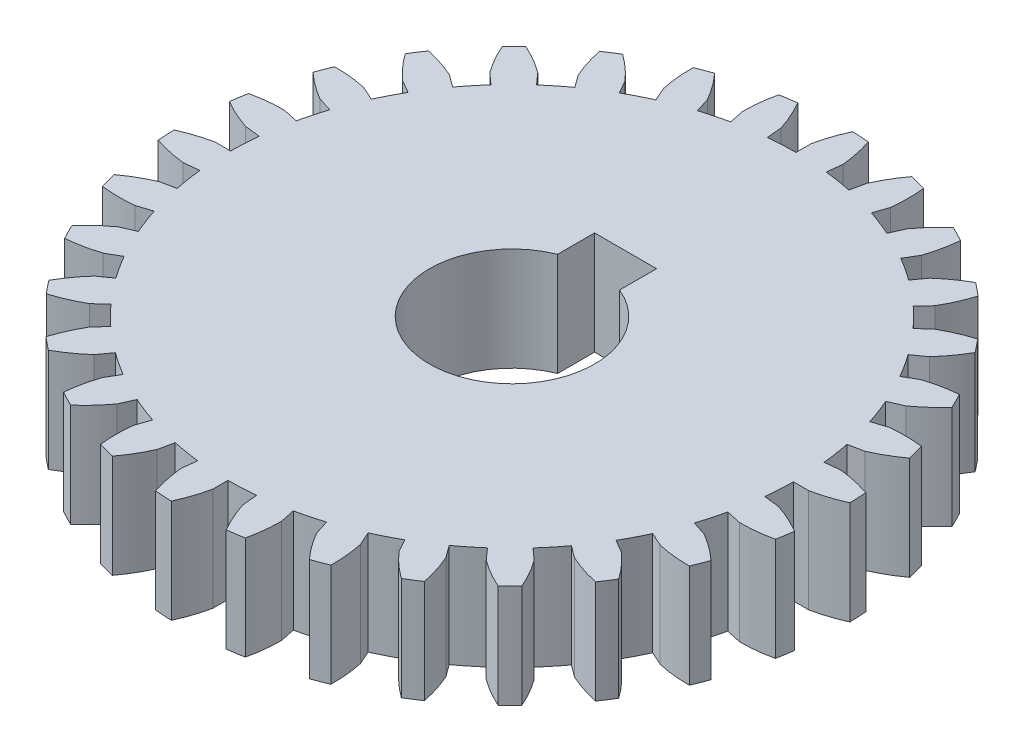
SolidWorks part; units mm, degrees
ref_plane "Front Plane" through (0, 0, 0) normal (0, 0, 1) x (1, 0, 0)
ref_plane "Top Plane" through (0, 0, 0) normal (0, 1, 0) x (1, 0, 0)
ref_plane "Right Plane" through (0, 0, 0) normal (1, 0, 0) x (0, 0, -1)
sketch "Sketch1" plane through (0, 0, 0) normal (0, 1, 0) x (1, 0, 0)
  circle A3 centre (0, 0) radius 13.75
  circle A4 centre (0, 0) radius 16
  circle A5 centre (0, 0) radius 15
  circle A6 centre (0, 0) radius 14
  circle A7 centre (0, 0) radius 14.4889
  dimension "pitch circle" = 30
  dimension "addendum circle" = 32
  dimension "root circle" = 27.5
  dimension "clearance circle" = 28
  dimension "base circle" = 28.9778
sketch "Sketch2" plane through (0, 0, 0) normal (0, 1, 0) x (1, 0, 0)
  line L0 (0, 0) -> (0, 14.4889)
  line L1 (0, 0) -> (7.2444, 12.5477) construction
  line L2 (0, 0) -> (12.5477, 7.2444) construction
  line L3 (0, 0) -> (14.4889, 0) construction
  line L4 (14.4889, 0) -> (14.4889, 22.7591) construction
  line L5 (12.5477, 7.2444) -> (4.9614, 20.3844) construction
  line L6 (7.2444, 12.5477) -> (0.6745, 16.3409) construction
  line L7 (0, 0) -> (3.1187, 14.6722)
  line L8 (0, 0) -> (1.5679, 14.9178) construction
  line L9 (0.8496, 14.9759) -> (0, 0) construction
  circle A0 centre (0, 0) radius 14.4889 construction
  circle A1 centre (0, 0) radius 15 construction
  arc A2 (1.5679, 14.9178) -> (0.1294, 14.9994) centre (0, 0) ccw
  spline S0 degree 3 poles (0, 14.4889) (1.2745, 20.4223) (9.5995, 22.7668) (14.4889, 22.7591) knots 0 0 0 0 1 1 1 1
  spline S1 degree 3 poles (1.6388, 14.3959) (1.0435, 20.4354) (-6.9629, 23.7065) (-11.8218, 24.2518) knots 0 0 0 0 1 1 1 1
  point P11 (0, 0)
  dimension "Involute Control" = 90
  dimension "Base circle quarter circumference" = 22.7591
  dimension "D1" = 15.1727
  dimension "D2" = 7.5864
  dimension "pitch circle" = 12
  dimension "Involute array" = 4
sketch "Sketch3" plane through (0, 0, 0) normal (0, 1, 0) x (1, 0, 0)
  line L0 (1.6388, 14.3959) -> (1.5552, 13.6618)
  line L1 (0, 0) -> (0, 14.4889) construction
  line L3 (0, 13.75) -> (0, 14.4889)
  arc A1 (0.502, 15.9921) -> (0, 14.4889) centre (7.0112, 12.9829) ccw
  circle A2 centre (0, 0) radius 16 construction
  circle A3 centre (0, 0) radius 13.75 construction
  arc A7 (1.6388, 14.3959) -> (1.31, 15.9463) centre (-5.4978, 13.6925) ccw
  arc A8 (1.5552, 13.6618) -> (0, 13.75) centre (0, 0) ccw
  arc A9 (1.31, 15.9463) -> (0.502, 15.9921) centre (0, 0) ccw
  circle A10 centre (0, 0) radius 14.4889 construction
  spline S0 degree 3 poles (1.6388, 14.3959) (1.0435, 20.4354) (-6.9629, 23.7065) (-11.8218, 24.2518) knots 0 0 0 0 1 1 1 1 construction
  spline S1 degree 3 poles (0, 14.4889) (1.2745, 20.4223) (9.5995, 22.7668) (14.4889, 22.7591) knots 0 0 0 0 1 1 1 1 construction
extrude "Boss-Extrude1" add sketch "Sketch3" along normal blind 5
sketch "Sketch5" plane through (0, 0, 0) normal (1, 0, 0) x (0, 0, -1)
  line L0 (0, 0) -> (0, 5.4709) construction
pattern_circular "CirPattern4" count 30 over 360 about axis through (0, 0, 0) along (0, 1, 0) of bodies 101
sketch "Sketch6" plane through (0, 0, 0) normal (0, 1, 0) x (1, 0, 0)
  circle A0 centre (0, 0) radius 13.75 construction
  circle A1 centre (0, 0) radius 13.75
extrude "Boss-Extrude2" add sketch "Sketch6" along normal up to surface (5 mm away) up to face at (2.2427, 5, 14.5662)
sketch "Sketch7" plane through (0, 5, 0) normal (0, 1, 0) x (1, 0, 0)
  line L1 (-1.5, 5.5) -> (1.5, 5.5)
  line L2 (-1.5, 5.5) -> (-1.5, 2.5)
  line L3 (-1.5, 2.5) -> (1.5, 2.5)
  line L4 (1.5, 5.5) -> (1.5, 2.5)
  line L5 (-1.5, 5.5) -> (1.5, 2.5) construction
  line L6 (-1.5, 2.5) -> (1.5, 5.5) construction
  circle A0 centre (0, 0) radius 4
  point P3 (0, 4)
  dimension "D1" = 8
  dimension "D2" = 3
extrude "Cut-Extrude1" cut sketch "Sketch7" against normal through all contours L2 A0 L4 L3 | L4 A0 L2 L3
equation "\"Module\"= 1"
equation "\"Teeth number\"= 30"
equation "\"Pressure angle\"= 15"
equation "\"pitch circle@Sketch1\"= \"Module\" * \"Teeth number\""
equation "\"addendum circle@Sketch1\"= \"pitch circle@Sketch1\" + ( \"Module\" * 2 )"
equation "\"root circle@Sketch1\"= \"pitch circle@Sketch1\" - ( ( \"Module\" * 1.25 ) * 2 )"
equation "\"clearance circle@Sketch1\"= \"pitch circle@Sketch1\" - ( \"Module\" * 2 )"
equation "\"base circle@Sketch1\"= \"pitch circle@Sketch1\" * cos ( \"Pressure angle\" )"
equation "\"D1@Sketch2\"=\"Base circle quarter circumference@Sketch2\"/3*2"
equation "\"D2@Sketch2\"=\"Base circle quarter circumference@Sketch2\"/3"
equation "\"pitch circle@Sketch2\"=360/\"Teeth number\""
equation "\"D1@CirPattern4\"=\"Teeth number\""
equation "\"Base circle quarter circumference@Sketch2\"= \"base circle@Sketch1\" * pi / 4"
